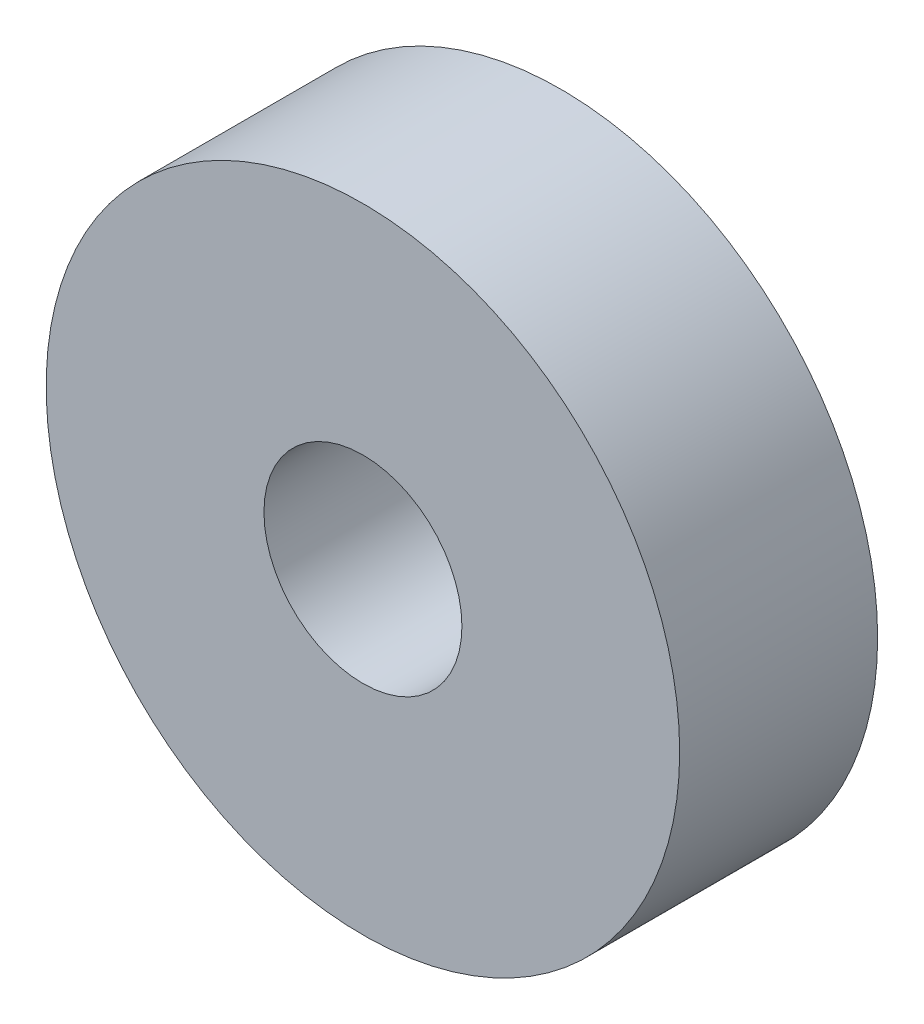
SolidWorks part; units mm, degrees
ref_plane "Plano frontal" through (0, 0, 0) normal (0, 0, 1) x (1, 0, 0)
ref_plane "Plano superior" through (0, 0, 0) normal (0, 1, 0) x (1, 0, 0)
ref_plane "Plano direito" through (0, 0, 0) normal (1, 0, 0) x (0, 0, -1)
sketch "Esboço1" plane through (0, 0, 0) normal (0, 0, 1) x (1, 0, 0)
  circle A0 centre (0, 0) radius 2.5
  circle A1 centre (0, 0) radius 8
extrude "Ressalto-extrusão1" add sketch "Esboço1" along normal blind 5
